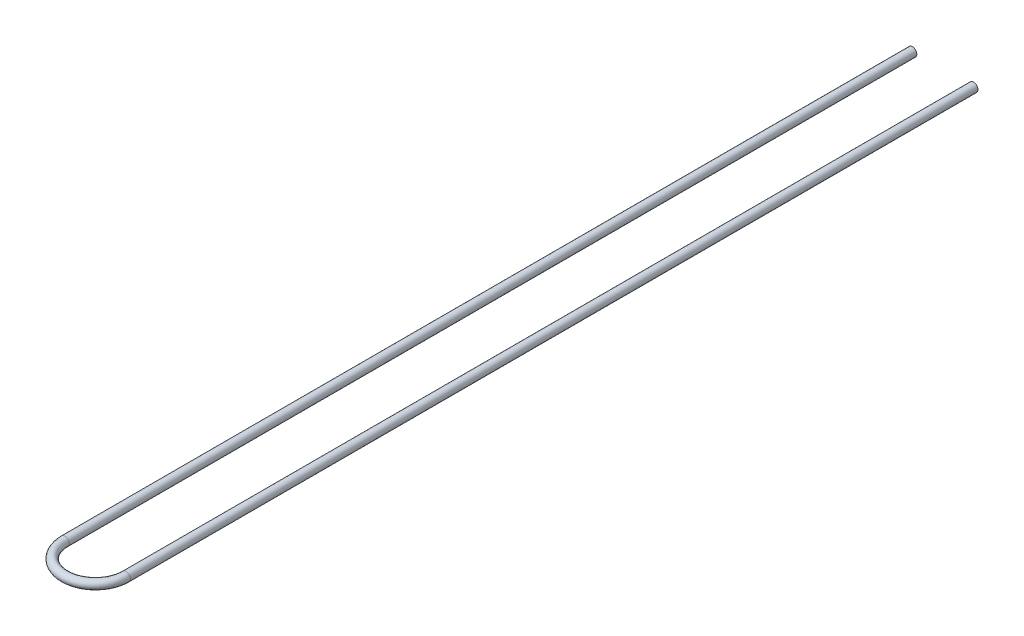
SolidWorks part; units mm, degrees
ref_plane "Front Plane" through (0, 0, 0) normal (0, 0, 1) x (1, 0, 0)
ref_plane "Top Plane" through (0, 0, 0) normal (0, 1, 0) x (1, 0, 0)
ref_plane "Right Plane" through (0, 0, 0) normal (1, 0, 0) x (0, 0, -1)
sketch "Sketch1" plane through (0, 0, 0) normal (0, 1, 0) x (1, 0, 0)
  line L0 (114.46, -300) -> (114.46, -2440)
  line L2 (-40, -300) -> (-40, -2440)
  arc A0 (-40, -2440) -> (114.46, -2440) centre (37.23, -2440) ccw
  dimension "D1" = 2140
  dimension "D2" = 154.46
ref_plane "Plane1" through (114.46, 0, 300) normal (0, 0, -1) x (-1, 0, 0)
sketch "Sketch2" plane through (114.46, 0, 300) normal (0, 0, -1) x (-1, 0, 0)
  circle A0 centre (0, 0) radius 9.95
  circle A1 centre (0, 0) radius 11.1
  dimension "D1" = 22.2
  dimension "D2" = 19.9
sweep "Sweep1" add profiles "Sketch2" path "Sketch1"
